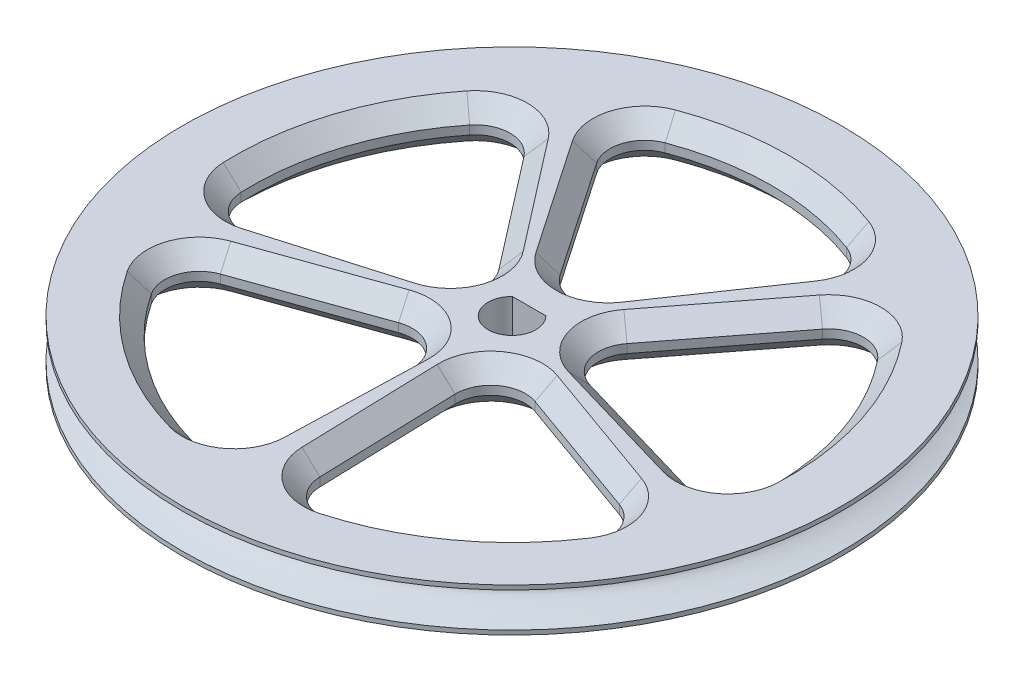
SolidWorks part; units mm, degrees
ref_plane "Front Plane" through (0, 0, 0) normal (0, 0, 1) x (1, 0, 0)
ref_plane "Top Plane" through (0, 0, 0) normal (0, 1, 0) x (1, 0, 0)
ref_plane "Right Plane" through (0, 0, 0) normal (1, 0, 0) x (0, 0, -1)
sketch "Sketch1" plane through (0, 0, 0) normal (0, 1, 0) x (1, 0, 0)
  circle A0 centre (0, 0) radius 24.13
  dimension "D1" = 48.26
extrude "Boss-Extrude1" add sketch "Sketch1" along normal blind 3.175
sketch "Sketch2" plane through (0, 3.175, 0) normal (0, 1, 0) x (1, 0, 0)
  line L0 (-1.2247, 1.25) -> (1.2247, 1.25)
  line L1 (0, 1.25) -> (0, -1.75) construction
  arc A0 (-1.2247, 1.25) -> (1.2247, 1.25) centre (0, 0) ccw
  dimension "D1" = 3.5
  dimension "D2" = 3
sketch "Sketch3" plane through (0, 3.175, 0) normal (0, 1, 0) x (1, 0, 0)
  line L0 (0, 0) -> (12.065, 20.8972) construction
  line L1 (0, 0) -> (-12.065, 20.8972) construction
  line L2 (-7.8503, 14.0438) -> (-2.098, 5.6144)
  line L3 (2.098, 5.6144) -> (7.8503, 14.0438)
  line L4 (0, 2.54) -> (0, 0) construction
  line L5 (0, 0) -> (0, 24.13) construction
  line L6 (10.9305, 11.8059) -> (4.6913, 3.7303)
  line L7 (5.988, -0.2604) -> (15.7823, -3.1264)
  line L8 (14.6058, -6.7473) -> (4.9974, -3.309)
  line L9 (1.6027, -5.7754) -> (1.9037, -15.976)
  line L10 (-1.9037, -15.976) -> (-1.6027, -5.7754)
  line L11 (-4.9974, -3.309) -> (-14.6058, -6.7473)
  line L12 (-15.7823, -3.1264) -> (-5.988, -0.2604)
  line L13 (-4.6913, 3.7303) -> (-10.9305, 11.8059)
  circle A0 centre (0, 0) radius 24.13 construction
  arc A1 (-6.6373, 17.8563) -> (6.6373, 17.8563) centre (0, 0) cw
  arc A2 (-2.098, 5.6144) -> (2.098, 5.6144) centre (0, 7.0462) ccw
  arc A3 (6.6373, 17.8563) -> (7.8503, 14.0438) centre (5.7523, 15.4755) cw
  arc A4 (-6.6373, 17.8563) -> (-7.8503, 14.0438) centre (-5.7523, 15.4755) ccw
  arc A5 (14.9314, 11.8303) -> (10.9305, 11.8059) centre (12.9405, 10.253) ccw
  arc A6 (14.9314, 11.8303) -> (19.0334, -0.7945) centre (0, 0) cw
  arc A7 (19.0334, -0.7945) -> (15.7823, -3.1264) centre (16.4956, -0.6886) cw
  arc A8 (4.6913, 3.7303) -> (5.988, -0.2604) centre (6.7013, 2.1774) ccw
  arc A9 (15.8654, -10.5448) -> (14.6058, -6.7473) centre (13.75, -9.1388) ccw
  arc A10 (15.8654, -10.5448) -> (5.126, -18.3474) centre (0, 0) cw
  arc A11 (5.126, -18.3474) -> (1.9037, -15.976) centre (4.4426, -15.9011) cw
  arc A12 (4.9974, -3.309) -> (1.6027, -5.7754) centre (4.1416, -5.7005) ccw
  arc A13 (-5.126, -18.3474) -> (-1.9037, -15.976) centre (-4.4426, -15.9011) ccw
  arc A14 (-5.126, -18.3474) -> (-15.8654, -10.5448) centre (0, 0) cw
  arc A15 (-15.8654, -10.5448) -> (-14.6058, -6.7473) centre (-13.75, -9.1388) cw
  arc A16 (-1.6027, -5.7754) -> (-4.9974, -3.309) centre (-4.1416, -5.7005) ccw
  arc A17 (-19.0334, -0.7945) -> (-15.7823, -3.1264) centre (-16.4956, -0.6886) ccw
  arc A18 (-19.0334, -0.7945) -> (-14.9314, 11.8303) centre (0, 0) cw
  arc A19 (-14.9314, 11.8303) -> (-10.9305, 11.8059) centre (-12.9405, 10.253) cw
  arc A20 (-5.988, -0.2604) -> (-4.6913, 3.7303) centre (-6.7013, 2.1774) ccw
  point P16 (9.525, 16.4978)
  point P19 (-9.525, 16.4978)
  point P59 (0, 0)
  point P60 (0, 0)
  dimension "D2" = 19.05
  dimension "D5" = 2.54
  dimension "D1" = 60
  dimension "D3" = 2.54
  dimension "D4" = 30
  dimension "D6" = 5
extrude "Cut-Extrude2" cut sketch "Sketch3" against normal through all
chamfer "Chamfer2" distance 1.27 angle 45 60 edges at (0, 3.175, -4.5062) (4.9742, 3.175, -9.8291) (8.1727, 3.175, -16.2456) (-4.9742, 3.175, -9.8291) (-8.1727, 3.175, -16.2456) (0, 3.175, -19.05) (-4.9742, 0, -9.8291) (-8.1727, 0, -16.2456) (0, 0, -19.05) (8.1727, 0, -16.2456) (4.9742, 0, -9.8291) (0, 0, -4.5062) (7.8109, 0, -7.7681) (12.925, 0, -12.7929) (18.1176, 0, -5.8868) (17.976, 0, 2.7526) (10.8851, 0, 1.6934) (4.2856, 0, -1.3925) (7.8109, 3.175, -7.7681) (12.925, 3.175, -12.7929) (18.1176, 3.175, -5.8868) (17.976, 3.175, 2.7526) (10.8851, 3.175, 1.6934) (4.2856, 3.175, -1.3925) (9.8016, 0, 5.0282) (16.1608, 0, 8.3392) (11.1973, 0, 15.4118) (2.937, 0, 17.9468) (1.7532, 0, 10.8757) (2.6487, 0, 3.6456) (9.8016, 3.175, 5.0282) (16.1608, 3.175, 8.3392) (11.1973, 3.175, 15.4118) (2.937, 3.175, 17.9468) (1.7532, 3.175, 10.8757) (2.6487, 3.175, 3.6456) (-1.7532, 0, 10.8757) (-2.937, 0, 17.9468) (-11.1973, 0, 15.4118) (-16.1608, 0, 8.3392) (-9.8016, 0, 5.0282) (-2.6487, 0, 3.6456) (-1.7532, 3.175, 10.8757) (-2.937, 3.175, 17.9468) (-11.1973, 3.175, 15.4118) (-16.1608, 3.175, 8.3392) (-9.8016, 3.175, 5.0282) (-2.6487, 3.175, 3.6456) (-10.8851, 0, 1.6934) (-17.976, 0, 2.7526) (-18.1176, 0, -5.8868) (-12.925, 0, -12.7929) (-7.8109, 0, -7.7681) (-4.2856, 0, -1.3925) (-10.8851, 3.175, 1.6934) (-17.976, 3.175, 2.7526) (-18.1176, 3.175, -5.8868) (-12.925, 3.175, -12.7929) (-7.8109, 3.175, -7.7681) (-4.2856, 3.175, -1.3925)
sketch "Sketch6" plane through (0, 0, 0) normal (1, 0, 0) x (0, 0, -1)
  line L0 (0, 5.8767) -> (0, -2.5924) construction
  line L1 (-24.13, 3.175) -> (-24.13, 0) construction
  line L2 (-24.13, 2.8575) -> (-24.13, 0.3175)
  line L4 (24.13, 3.175) -> (-24.13, 3.175) construction
  spline S0 degree 2 poles (-24.13, 2.8575) (-20.066, 1.5875) (-24.13, 0.3175) knots 0 0 0 1 1 1
  dimension "D2" = 1.5875
  dimension "D1" = 2.032
  dimension "D3" = 1.27
  dimension "D4" = 1.27
revolve "Cut-Revolve3" cut sketch "Sketch6" angle 360 about L0
extrude "Cut-Extrude4" cut sketch "Sketch2" against normal blind 3.175
